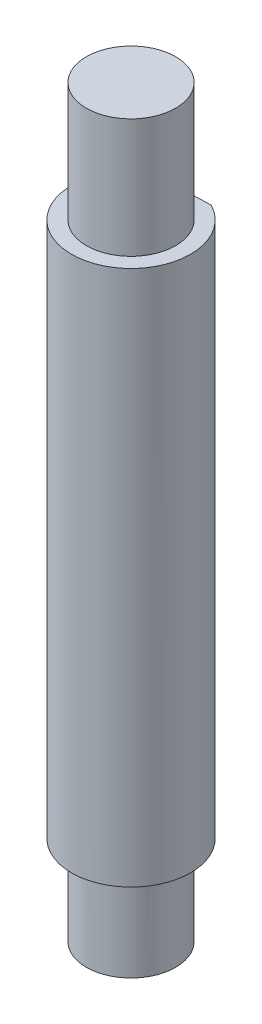
SolidWorks part; units mm, degrees
ref_plane "前视基准面" through (0, 0, 0) normal (0, 0, 1) x (1, 0, 0)
ref_plane "上视基准面" through (0, 0, 0) normal (0, 1, 0) x (1, 0, 0)
ref_plane "右视基准面" through (0, 0, 0) normal (1, 0, 0) x (0, 0, -1)
sketch "草图1" plane through (0, 0, 0) normal (0, 1, 0) x (1, 0, 0)
  circle A0 centre (0, 0) radius 1.5
extrude "凸台-拉伸1" add sketch "草图1" along normal blind 25
ref_plane "基准面1" through (0, 18, 0) normal (0, -1, 0) x (-1, 0, 0)
sketch "草图2" plane through (0, 18, 0) normal (0, -1, 0) x (-1, 0, 0)
  circle A0 centre (0, 0) radius 1.5
  circle A1 centre (0, 0) radius 2
extrude "凸台-拉伸2" add sketch "草图2" along normal blind 15
sketch "草图3" plane through (0, 18, 0) normal (0, 1, 0) x (1, 0, 0)
  line L1 (0.9163, 1.7778) -> (-1.0222, 1.719)
  circle A0 centre (0, 0) radius 1.5
  arc A1 (-1.0222, 1.719) -> (0.9163, 1.7778) centre (0, 0) ccw
extrude "凸台-拉伸3" add sketch "草图3" along normal blind 3
